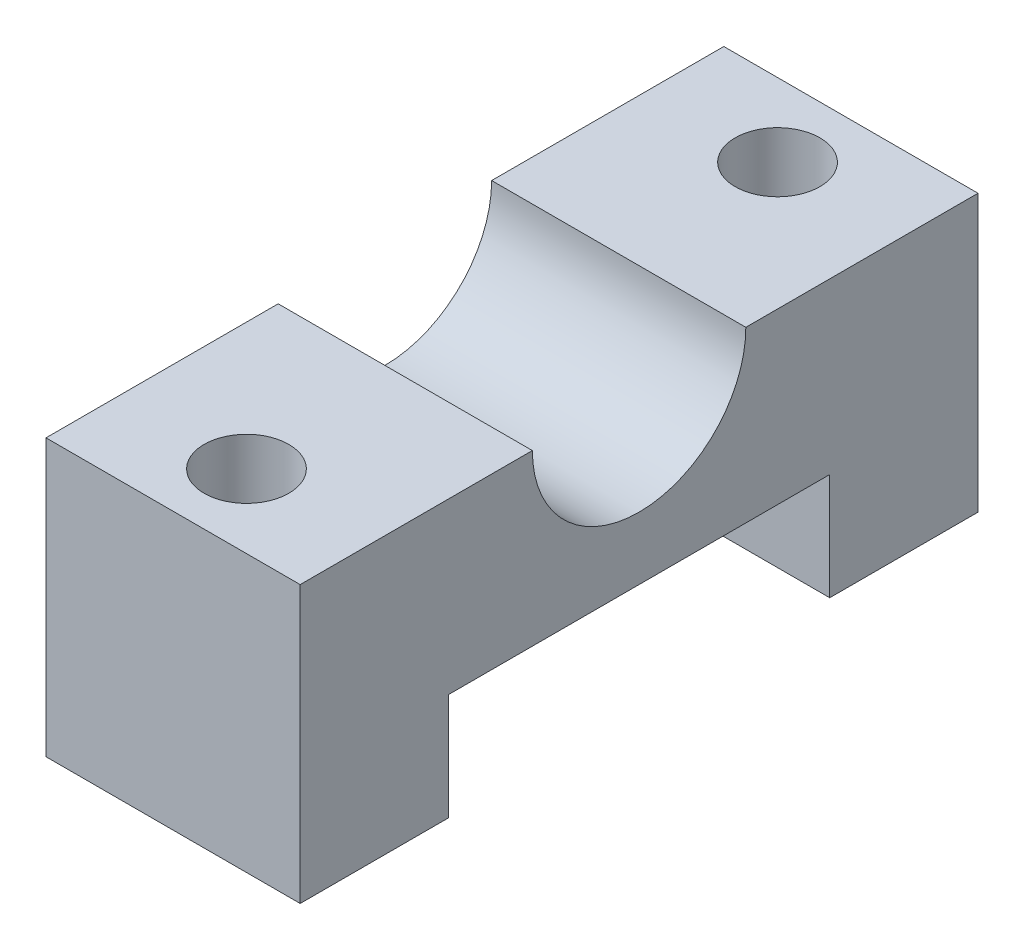
SolidWorks part; units mm, degrees
ref_plane "Front Plane" through (0, 0, 0) normal (0, 0, 1) x (1, 0, 0)
ref_plane "Top Plane" through (0, 0, 0) normal (0, 1, 0) x (1, 0, 0)
ref_plane "Right Plane" through (0, 0, 0) normal (1, 0, 0) x (0, 0, -1)
sketch "Sketch1" plane through (0, 0, 0) normal (1, 0, 0) x (0, 0, -1)
  line L0 (4, 0) -> (12.7, 0)
  line L1 (-12.7, 0) -> (-4, 0)
  line L2 (-12.7, 0) -> (-12.7, -10.35)
  line L3 (-12.7, -10.35) -> (12.7, -10.35)
  line L4 (12.7, 0) -> (12.7, -10.35)
  arc A0 (-4, 0) -> (4, 0) centre (0, 0) ccw
  dimension "D1" = 8
  dimension "D3" = 10.35
  dimension "D4" = 12.7
  dimension "D2" = 25.4
  dimension "D5" = 0
extrude "Boss-Extrude1" add sketch "Sketch1" along normal blind 9.525
sketch "Sketch3" plane through (9.525, 0, 0) normal (1, 0, 0) x (0, 0, -1)
  line L0 (-12.7, -10.35) -> (12.7, -10.35) construction
  line L1 (-7.1437, -6.35) -> (7.1438, -6.35)
  line L2 (-7.1437, -6.35) -> (-7.1437, -10.35)
  line L3 (-7.1437, -10.35) -> (7.1437, -10.35)
  line L4 (7.1438, -6.35) -> (7.1437, -10.35)
  dimension "D1" = 14.2875
  dimension "D2" = 7.1437
  dimension "D3" = 4
  dimension "D4" = 0
extrude "Cut-Extrude1" cut sketch "Sketch3" against normal through all
sketch "Sketch4" plane through (0, -10.35, 0) normal (0, -1, 0) x (1, 0, 0)
  line L3 (9.525, -12.7) -> (0, -12.7) construction
  line L5 (9.525, 12.7) -> (9.525, 7.1437) construction
  line L6 (9.525, -7.1438) -> (9.525, -12.7) construction
  line L7 (9.525, 12.7) -> (0, 12.7) construction
  circle A0 centre (4.7625, -9.95) radius 1.5875
  circle A1 centre (4.7625, 9.95) radius 1.5875
  dimension "D1" = 3.175
  dimension "D4" = 3.175
  dimension "D3" = 2.75
  dimension "D2" = 4.7625
  dimension "D5" = 4.7625
  dimension "D6" = 2.75
extrude "Cut-Extrude2" cut sketch "Sketch4" against normal through all
equation "\"D4@Sketch1\"=\"D2@Sketch1\"/2"
equation "\"D2@Sketch3\"=\"D1@Sketch3\"/2"
equation "\"D4@Sketch4\"=\"D1@Sketch4\""
equation "\"D2@Sketch4\"=\"D5@Sketch4\""
equation "\"D6@Sketch4\"=\"D3@Sketch4\""
